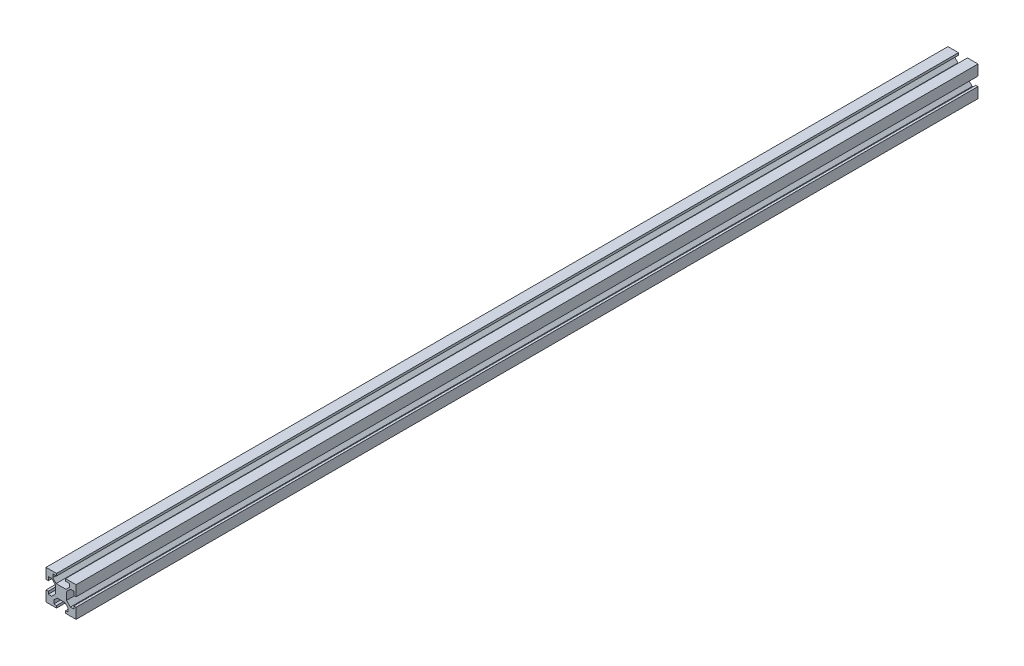
SolidWorks part; units mm, degrees
ref_plane "Front Plane" through (0, 0, 0) normal (0, 0, 1) x (1, 0, 0)
ref_plane "Top Plane" through (0, 0, 0) normal (0, 1, 0) x (1, 0, 0)
ref_plane "Right Plane" through (0, 0, 0) normal (1, 0, 0) x (0, 0, -1)
sketch "Sketch1" plane through (0, 0, 0) normal (0, 0, 1) x (1, 0, 0)
  line L0 (-10, 3) -> (-10, 10)
  line L1 (10, -10) -> (-10, -10) construction
  line L2 (10, -10) -> (10, 10) construction
  line L3 (10, 10) -> (-10, 10) construction
  line L4 (-10, -10) -> (-10, 10) construction
  line L5 (10, -10) -> (-10, 10) construction
  line L6 (10, 10) -> (-10, -10) construction
  line L7 (-10, 10) -> (-3, 10)
  line L8 (-3, 10) -> (-3, 8.5)
  line L9 (-3, 8.5) -> (-5.5, 8.5)
  line L10 (-5.5, 8.5) -> (-5.5, 6.2071)
  line L11 (-5.5, 6.2071) -> (-3.2929, 4)
  line L12 (0, 14.0643) -> (0, -17.0468) construction
  line L13 (-3.2929, 4) -> (3.2929, 4)
  line L14 (-10, 3) -> (-8.5, 3)
  line L15 (-8.5, 3) -> (-8.5, 5.5)
  line L16 (-8.5, 5.5) -> (-6.2071, 5.5)
  line L17 (-6.2071, 5.5) -> (-3.6457, 2.9386)
  line L18 (-3.6457, 2.9386) -> (-3.6457, -2.2314)
  line L19 (-10, -10) -> (-10, -3)
  line L20 (-10, -3) -> (-8.5, -3)
  line L21 (-8.5, -3) -> (-8.5, -4.7929)
  line L22 (-8.5, -4.7929) -> (-6.2071, -4.7929)
  line L23 (-6.2071, -4.7929) -> (-3.6457, -2.2314)
  line L24 (-10, -10) -> (-3, -10)
  line L25 (-3, -10) -> (-3, -8.5)
  line L26 (-3, -8.5) -> (-4.7929, -8.5)
  line L27 (-4.7929, -8.5) -> (-4.7929, -6.2071)
  line L28 (13.2183, 0) -> (-13.2183, 0) construction
  line L29 (-4.7929, -6.2071) -> (-2.5858, -4)
  line L30 (-2.5858, -4) -> (2.5858, -4)
  line L31 (4.7929, -6.2071) -> (2.5858, -4)
  line L32 (4.7929, -8.5) -> (4.7929, -6.2071)
  line L33 (3, -8.5) -> (4.7929, -8.5)
  line L34 (3, -10) -> (3, -8.5)
  line L35 (10, -10) -> (3, -10)
  line L36 (6.2071, -4.7929) -> (3.6457, -2.2314)
  line L37 (8.5, -4.7929) -> (6.2071, -4.7929)
  line L38 (8.5, -3) -> (8.5, -4.7929)
  line L39 (10, -3) -> (8.5, -3)
  line L40 (10, -10) -> (10, -3)
  line L41 (3.6457, 2.9386) -> (3.6457, -2.2314)
  line L42 (6.2071, 5.5) -> (3.6457, 2.9386)
  line L43 (8.5, 5.5) -> (6.2071, 5.5)
  line L44 (8.5, 3) -> (8.5, 5.5)
  line L45 (10, 3) -> (8.5, 3)
  line L46 (5.5, 6.2071) -> (3.2929, 4)
  line L47 (5.5, 8.5) -> (5.5, 6.2071)
  line L48 (3, 8.5) -> (5.5, 8.5)
  line L49 (3, 10) -> (3, 8.5)
  line L50 (10, 10) -> (3, 10)
  line L51 (10, 3) -> (10, 10)
  point P0 (0, 0)
  point P30 (0, 0)
  point P33 (0, -4)
  point P49 (0, 4)
  dimension "D1" = 20
  dimension "D2" = 20
  dimension "D3" = 7
  dimension "D4" = 1
  dimension "D5" = 1.5
  dimension "D6" = 1
  dimension "D7" = 8
  dimension "D8" = 5.17
  dimension "D9" = 4.5
extrude "Boss-Extrude1" add sketch "Sketch1" against normal blind 600
